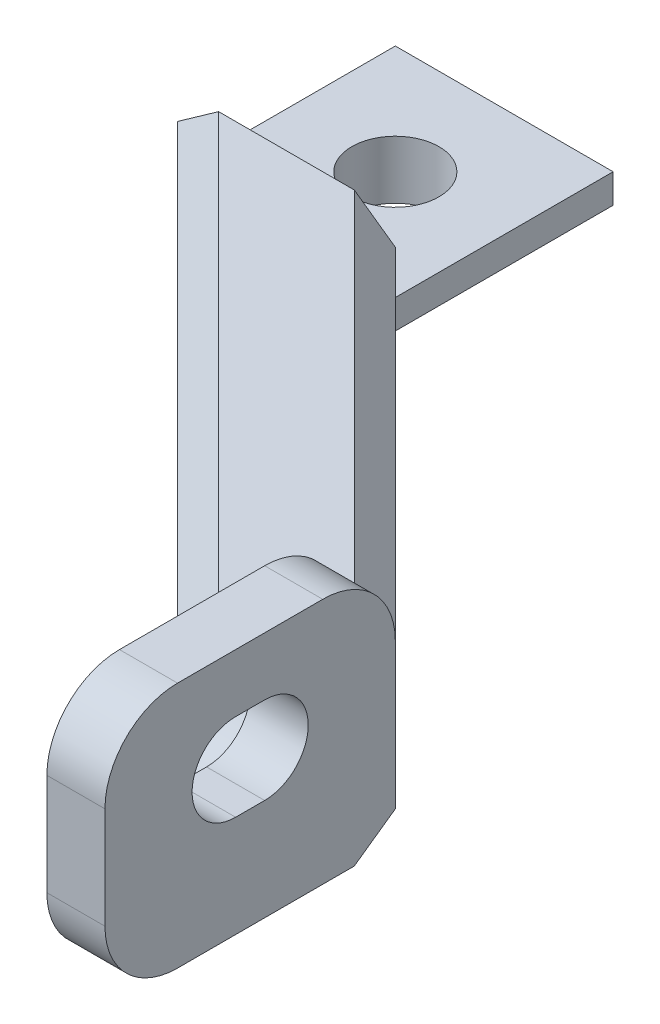
SolidWorks part; units mm, degrees
ref_plane "Front Plane" through (0, 0, 0) normal (0, 0, 1) x (1, 0, 0)
ref_plane "Top Plane" through (0, 0, 0) normal (0, 1, 0) x (1, 0, 0)
ref_plane "Right Plane" through (0, 0, 0) normal (1, 0, 0) x (0, 0, -1)
sketch "Sketch1" plane through (0, 0, 0) normal (0, 1, 0) x (1, 0, 0)
  line L0 (7.5, -7.5) -> (36, -36)
  line L1 (-7.5, 7.5) -> (7.5, 7.5)
  line L2 (-7.5, 7.5) -> (-7.5, -7.5)
  line L3 (-7.5, -7.5) -> (7.5, -7.5) construction
  line L4 (7.5, 7.5) -> (7.5, -7.5)
  line L5 (-7.5, 7.5) -> (7.5, -7.5) construction
  line L6 (-7.5, -7.5) -> (7.5, 7.5) construction
  line L7 (-7.5, -7.5) -> (36, -51)
  line L8 (36, -51) -> (36, -36)
  point P0 (0, 0)
  dimension "D1" = 15
  dimension "D2" = 135
  dimension "D3" = 28.5
extrude "Boss-Extrude1" add sketch "Sketch1" along normal blind 9
sketch "Sketch2" plane through (0, 0, 0) normal (0, -1, 0) x (1, 0, 0)
  line L1 (36, 36) -> (32, 36)
  line L2 (36, 36) -> (36, 56)
  line L3 (36, 56) -> (32, 56)
  line L4 (32, 36) -> (32, 56)
  dimension "D1" = 4
  dimension "D2" = 20
extrude "Boss-Extrude2" add sketch "Sketch2" against normal blind 17
sketch "Sketch3" plane through (7.5, 0, 0) normal (1, 0, 0) x (0, 0, -1)
  line L0 (7.5, 9) -> (7.5, 0) construction
  line L1 (-7.5, 9) -> (7.5, 9)
  line L2 (-7.5, 9) -> (-7.5, 4)
  line L3 (-7.5, 4) -> (7.5, 4)
  line L4 (7.5, 9) -> (7.5, 4)
  line L5 (-7.5, 0) -> (7.5, 0) construction
  dimension "D1" = 4
extrude "Cut-Extrude1" cut sketch "Sketch3" against normal through all
sketch "Sketch4" plane through (0, 4, 0) normal (0, 1, 0) x (1, 0, 0)
  circle A0 centre (0, 0) radius 3
  dimension "D1" = 6
extrude "Cut-Extrude2" cut sketch "Sketch4" against normal through all
sketch "Sketch5" plane through (36, 0, 0) normal (1, 0, 0) x (0, 0, -1)
  line L0 (-46, 17) -> (-46, 0) construction
  line L3 (-56, 8.5) -> (-36, 8.5) construction
  line L6 (-45, 10) -> (-47, 10) construction
  line L7 (-45, 7) -> (-47, 7)
  line L8 (-45, 13) -> (-47, 13)
  line L10 (-56, 17) -> (-56, 0) construction
  line L11 (-36, 9) -> (-36, 0) construction
  line L12 (-56, 0) -> (-36, 0) construction
  line L13 (-36, 17) -> (-56, 17) construction
  arc A0 (-45, 7) -> (-45, 13) centre (-45, 10) ccw
  arc A1 (-47, 13) -> (-47, 7) centre (-47, 10) ccw
  point P4 (-56, 8.5)
  point P11 (-46, 0)
  point P14 (-46, 10)
  dimension "D1" = 6
  dimension "D2" = 4
  dimension "D3" = 2
extrude "Cut-Extrude3" cut sketch "Sketch5" against normal through all
sketch "Sketch6" plane through (32, 0, 0) normal (-1, 0, 0) x (0, 0, 1)
  line L0 (47, 7) -> (45, 7) construction
  line L1 (47, 7) -> (45, 7)
  line L3 (47, 13) -> (45, 13)
  line L4 (47, 5) -> (45, 5)
  line L5 (47, 15) -> (45, 15)
  arc A0 (42.1716, 9) -> (45, 7) centre (45, 10) ccw construction
  arc A1 (47, 7) -> (49.8284, 9) centre (47, 10) ccw construction
  arc A2 (42.1716, 9) -> (45, 7) centre (45, 10) ccw
  arc A3 (47, 7) -> (49.8284, 9) centre (47, 10) ccw
  arc A6 (45, 13) -> (42.1716, 9) centre (45, 10) ccw
  arc A7 (49.8284, 9) -> (47, 13) centre (47, 10) ccw
  arc A8 (40.286, 8.3333) -> (45, 5) centre (45, 10) ccw
  arc A9 (45, 15) -> (40.286, 8.3333) centre (45, 10) ccw
  arc A10 (51.714, 8.3333) -> (47, 15) centre (47, 10) ccw
  arc A11 (47, 5) -> (51.714, 8.3333) centre (47, 10) ccw
  dimension "D1" = 2
extrude "Cut-Extrude4" cut sketch "Sketch6" along normal through all
fillet "Fillet1" radius 5 3 edges at (34, 17, 36) (34, 0, 56) (34, 17, 56)
chamfer "Chamfer1" distance 2 angle 45 7 edges at (21.75, 0, 21.75) (7.5, 0, 0) (0, 0, -7.5) (-7.5, 0, 0) (12.25, 0, 27.25) (8.8005, 9, 23.8005) (21.75, 9, 21.75)
